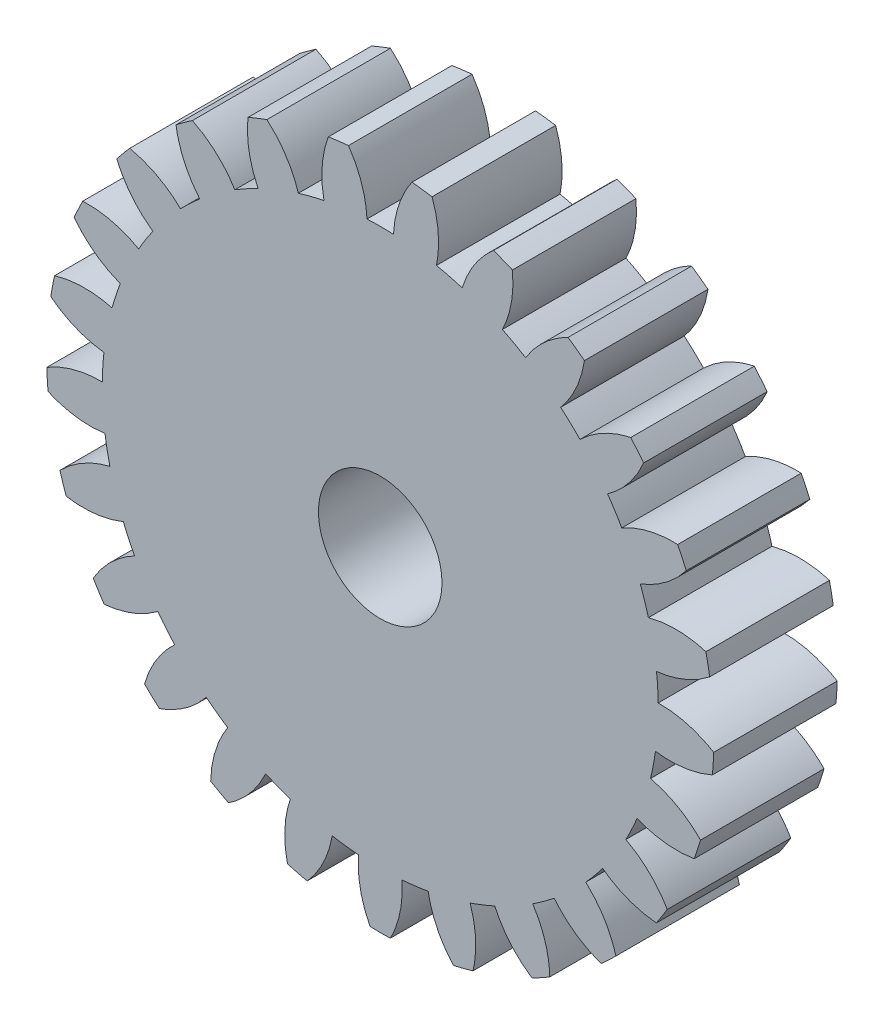
SolidWorks part; units mm, degrees
ref_plane "Front Plane" through (0, 0, 0) normal (0, 0, 1) x (1, 0, 0)
ref_plane "Top Plane" through (0, 0, 0) normal (0, 1, 0) x (1, 0, 0)
ref_plane "Right Plane" through (0, 0, 0) normal (1, 0, 0) x (0, 0, -1)
sketch "Sketch1" plane through (0, 0, 0) normal (0, 0, 1) x (1, 0, 0)
  circle A0 centre (0, 0) radius 25
  circle A1 centre (0, 0) radius 27
  circle A2 centre (0, 0) radius 22.5
  dimension "D1" = 50
  dimension "D2" = 54
  dimension "D3" = 4.5
extrude "Boss-Extrude1" add sketch "Sketch1" along normal mid plane 10 contours A1
sketch "Sketch2" plane through (0, 0, 0) normal (0, 1, 0) x (1, 0, 0)
  line L0 (0, -5) -> (0, 5)
  line L1 (-27, -5) -> (27, -5) construction
  line L2 (27, 5) -> (-27, 5) construction
  line L3 (0, 0) -> (0, 5) construction
  dimension "D1" = 0
sketch "Sketch3" plane through (0, 0, 0) normal (0, 0, 1) x (1, 0, 0)
  line L0 (0, 0) -> (0, 27) construction
  line L1 (-1.5698, 24.9507) -> (1.5698, 24.9507) construction
  line L2 (-1.072, 22.4744) -> (0, 0) construction
  line L3 (0, 20.6378) -> (-2.6344, 27.8758) construction
  line L4 (0, 0) -> (3.384, 26.7871) construction
  line L5 (1.5698, 24.9507) -> (4.6845, 24.5572) construction
  arc A1 (-1.072, 22.4744) -> (-3.3153, 27.803) centre (-9.4743, 22.0737) ccw
  arc A2 (1.072, 22.4744) -> (3.3153, 27.803) centre (9.4743, 22.0737) cw
  circle A3 centre (0, 0) radius 22.5 construction
  arc A5 (1.072, 22.4744) -> (-1.072, 22.4744) centre (0, 0) ccw
  circle A7 centre (0, 0) radius 25 construction
  circle A8 centre (0, 0) radius 28
  arc A9 (3.3153, 27.803) -> (-3.3153, 27.803) centre (0, 0) ccw
  circle A10 centre (0, 0) radius 27 construction
  dimension "D2" = 20
  dimension "D3" = 7.2
  dimension "D1" = 1
curve "Curve1"
sketch "Sketch4" plane through (0, 0, 5) normal (0, 0, 1) x (1, 0, 0)
  line L0 (0, 0) -> (0, 27) construction
  line L1 (-1.5698, 24.9507) -> (1.5698, 24.9507) construction
  line L2 (-1.072, 22.4744) -> (0, 0) construction
  line L3 (0, 20.6378) -> (-2.6344, 27.8758) construction
  line L4 (0, 0) -> (3.384, 26.7871) construction
  line L5 (1.5698, 24.9507) -> (4.6845, 24.5572) construction
  circle A0 centre (0, 0) radius 27 construction
  arc A1 (-1.072, 22.4744) -> (-3.3153, 27.803) centre (-9.4743, 22.0737) ccw
  arc A2 (1.072, 22.4744) -> (3.3153, 27.803) centre (9.4743, 22.0737) cw
  arc A5 (1.072, 22.4744) -> (-1.072, 22.4744) centre (0, 0) ccw
  arc A9 (3.3153, 27.803) -> (-3.3153, 27.803) centre (0, 0) ccw
sketch "Sketch5" plane through (0, 0, -5) normal (0, 0, 1) x (1, 0, 0)
  line L0 (0, 0) -> (0, 27) construction
  line L1 (-1.5698, 24.9507) -> (1.5698, 24.9507) construction
  line L2 (-1.072, 22.4744) -> (0, 0) construction
  line L3 (0, 20.6378) -> (-2.6344, 27.8758) construction
  line L4 (0, 0) -> (3.384, 26.7871) construction
  line L5 (1.5698, 24.9507) -> (4.6845, 24.5572) construction
  arc A1 (-1.072, 22.4744) -> (-3.3153, 27.803) centre (-9.4743, 22.0737) ccw
  arc A2 (1.072, 22.4744) -> (3.3153, 27.803) centre (9.4743, 22.0737) cw
  arc A5 (1.072, 22.4744) -> (-1.072, 22.4744) centre (0, 0) ccw
  arc A9 (3.3153, 27.803) -> (-3.3153, 27.803) centre (0, 0) ccw
loft "Cut-Loft1" cut profiles "Sketch4", "Sketch3", "Sketch5"
pattern_circular "CirPattern1" count 25 over 360 about axis through (0, 0, 5) along (0, 0, -1) of "Cut-Loft1"
sketch "Sketch6" plane through (0, 0, 5) normal (0, 0, 1) x (1, 0, 0)
  circle A0 centre (0, 0) radius 5
  dimension "D1" = 10
extrude "Cut-Extrude1" cut sketch "Sketch6" against normal through all
equation "\"Modulus\"= 2mm"
equation "\"Number of Teeth\"= 25"
equation "\"D1@Sketch1\"=\"Modulus\"*\"Number of Teeth\""
equation "\"D2@Sketch1\"=(\"Number of Teeth\"+2) * \"Modulus\""
equation "\"D3@Sketch1\"=\"Modulus\" * if(\"Modulus\"=>1.25 , 2.25, 2.4)"
equation "\"D3@Sketch3\"=180 /  \"Number of Teeth\""
equation "\"Helix Angle\" = 0deg"
equation "\"D1@Sketch2\"=\"Helix Angle\""
equation "\"D1@CirPattern1\"=\"Number of Teeth\""
equation "\"Gear Thickness\"= 10mm"
equation "\"Boar Diameter\"= 10mm"
equation "\"D1@Boss-Extrude1\"=\"Gear Thickness\""
